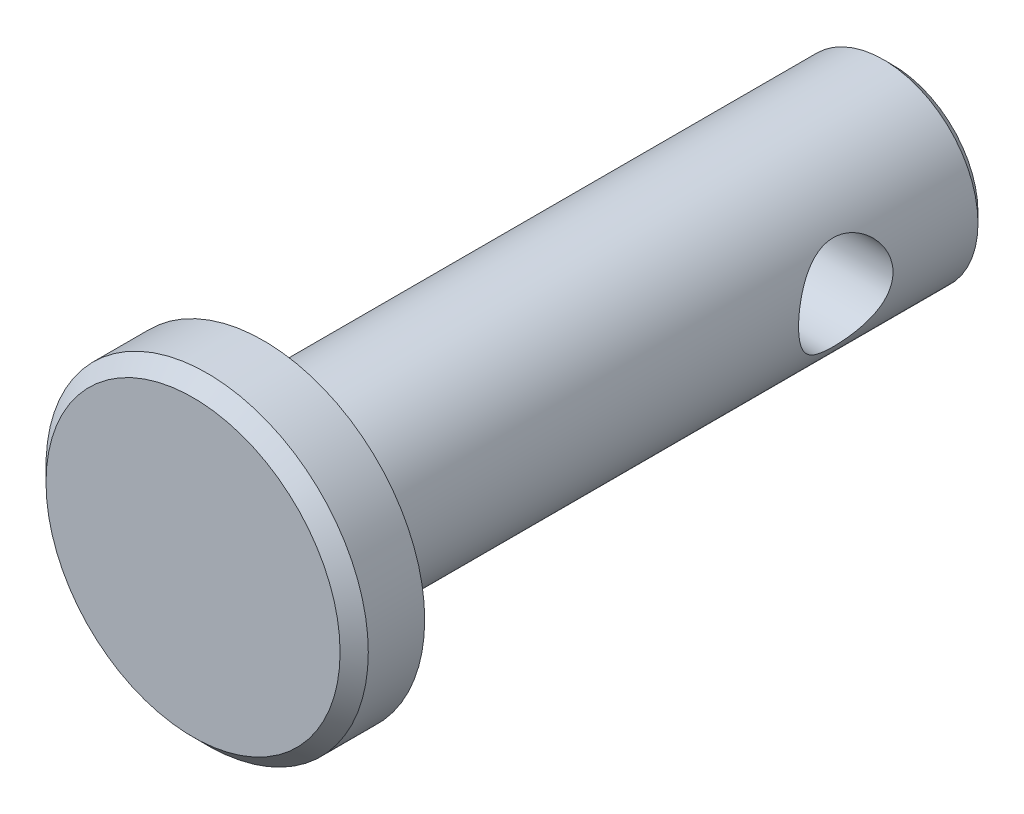
SolidWorks part; units mm, degrees
ref_plane "Front" through (0, 0, 0) normal (0, 0, 1) x (1, 0, 0)
ref_plane "Top" through (0, 0, 0) normal (0, 1, 0) x (1, 0, 0)
ref_plane "Right" through (0, 0, 0) normal (1, 0, 0) x (0, 0, -1)
sketch "Sketch1" plane through (0, 0, 0) normal (0, 0, 1) x (1, 0, 0)
  circle A0 centre (0, 0) radius 2.3812
  point P3 (0, 2.3812)
  point P4 (0, -2.3812)
  dimension "dia" = 4.7625
extrude "Extrude1" add sketch "Sketch1" along normal mid plane 15.875
sketch "Sketch2" plane through (0, 0, 7.9375) normal (0, 0, 1) x (1, 0, 0)
  circle A0 centre (0, 0) radius 4.064
  dimension "head dia" = 8.128
extrude "Extrude2" add sketch "Sketch2" along normal blind 1.778
chamfer "Chamfer1" distance 0.3556 angle 45 1 edges at (4.064, 0, 9.7155)
sketch "Sketch3" plane through (0, 0, 0) normal (1, 0, 0) x (0, 0, -1)
  line L0 (-7.9375, -2.3812) -> (-7.9375, 2.3812) construction
  circle A0 centre (4.3656, 0) radius 1.1906
  point P2 (3.175, 0)
  dimension "hole dia" = 2.3813
  dimension "useable Lg" = 11.1125
extrude "Extrude3" cut sketch "Sketch3" against normal through all and the other way through all
chamfer "Chamfer2" distance 0.2381 angle 45 1 edges at (2.3812, 0, -7.9375)
ref_plane "Plane1" through (0, 0, -4.3656) normal (0, 0, 1) x (1, 0, 0)
sketch "Sketch8" plane through (0, 0, 0) normal (1, 0, 0) x (0, 0, -1)
  line L0 (-9.7155, 3.7084) -> (-9.7155, -3.7084) construction
  line L1 (-9.3599, -4.064) -> (-7.9375, -4.064) construction
  line L2 (7.9375, -2.1431) -> (7.9375, 2.1431) construction
  point P0 (-9.7155, 4.064)
  point P1 (-7.9375, 4.064)
  point P5 (7.9375, 2.3812)
  point P8 (-9.7155, -4.064)
  point P9 (7.9375, -2.3812)
equation "\"D1@Chamfer1\" = \"head ht@Extrude2\" * .2"
equation "\"D1@Chamfer2\" = \"dia@Sketch1\" * .05"
